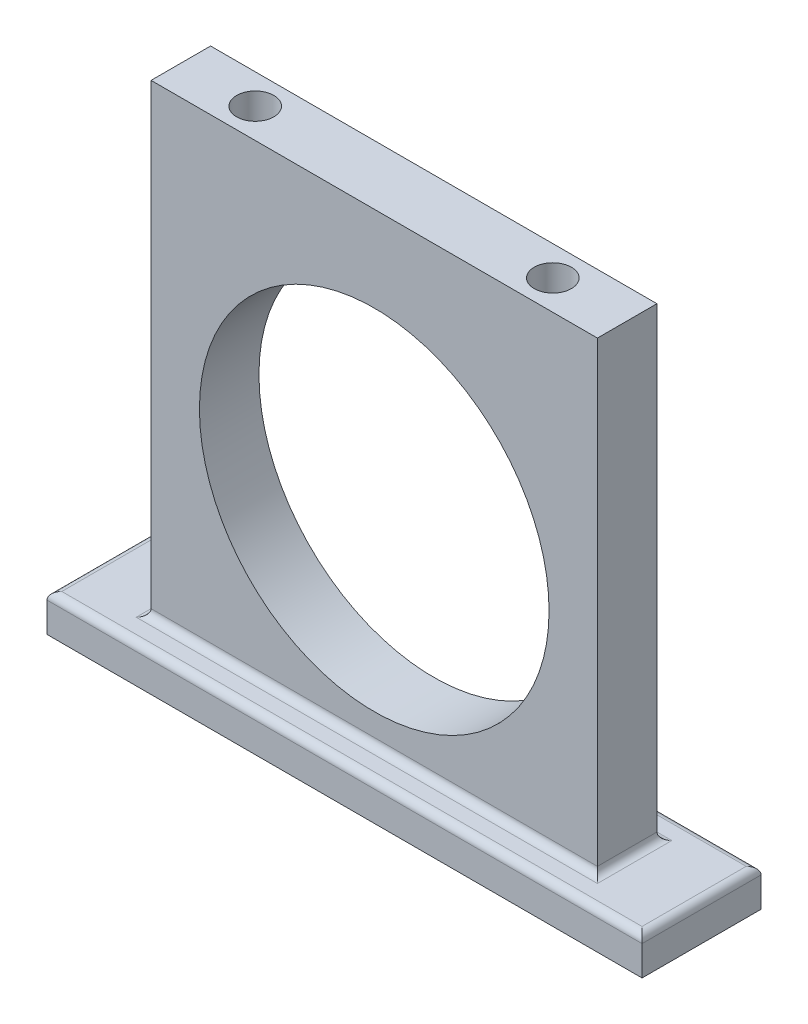
SolidWorks part; units mm, degrees
ref_plane "前视基准面" through (0, 0, 0) normal (0, 0, 1) x (1, 0, 0)
ref_plane "上视基准面" through (0, 0, 0) normal (0, 1, 0) x (1, 0, 0)
ref_plane "右视基准面" through (0, 0, 0) normal (1, 0, 0) x (0, 0, -1)
sketch "草图1" plane through (0, 0, 0) normal (0, 0, 1) x (1, 0, 0)
  line L0 (30, -32.5) -> (-30, -32.5)
  line L1 (-30, 0) -> (-30, -32.5)
  line L2 (-30, 0) -> (-30, 35)
  line L3 (-30, 35) -> (30, 35)
  line L4 (30, 35) -> (30, -32.5)
  line L5 (0, 35) -> (0, -47.189) construction
  circle A0 centre (0, 0) radius 23.5
  dimension "D1" = 32.5
  dimension "D3" = 60
  dimension "D2" = 35
extrude "凸台-拉伸1" add sketch "草图1" along normal blind 8
sketch "草图2" plane through (30, 0, 0) normal (1, 0, 0) x (0, 0, -1)
  line L0 (-4, -32.5) -> (-4, -46.3378) construction
  line L1 (-8, -32.5) -> (0, -32.5) construction
  line L3 (-12, -32.5) -> (4, -32.5)
  line L4 (-12, -32.5) -> (-12, -27.5)
  line L5 (-12, -27.5) -> (4, -27.5)
  line L6 (4, -32.5) -> (4, -27.5)
  point P8 (-4, -32.5)
extrude "凸台-拉伸2" add sketch "草图2" against normal blind 70
ref_plane "基准面4" through (0, 0, 0) normal (-1, 0, 0) x (0, 0, 1)
mirror "镜向1" about plane through (0, 0, 0) normal (-1, 0, 0) of "凸台-拉伸2"
fillet "圆角2" radius 1 8 edges at (0, -27.5, 12) (-40, -27.5, 4) (0, -27.5, -4) (40, -27.5, 4) (-30, -27.5, 4) (0, -27.5, 8) (30, -27.5, 4) (0, -27.5, 0)
sketch "草图3" plane through (0, 35, 0) normal (0, 1, 0) x (1, 0, 0)
  line L0 (-30, -4) -> (36.4193, -4) construction
  line L1 (-30, -8) -> (-30, 0) construction
  line L2 (-20, -22.8958) -> (-20, 13.0558)
  line L3 (0, -8) -> (0, 10.9623) construction
  line L4 (30, -8) -> (-30, -8) construction
  line L5 (20, -22.8958) -> (20, 13.0558)
  dimension "D1" = 20
ref_point "点1"
ref_point "点2"
hole_wizard "M6 螺纹孔1" positions "草图13" profile "草图14" tap size "M6" standard "GB"
sketch "草图13" plane through (0, 35, 0) normal (0, 1, 0) x (1, 0, 0)
  point P0 (-20, -4)
  point P3 (20, -4)
sketch "草图14" plane through (-20, 35, 4) normal (1, 0, 0) x (0, 0, 1)
  line L0 (0, 0) -> (0, 8.5022)
  line L1 (0, 8.5022) -> (2.5, 7)
  line L2 (2.5, 7) -> (2.5, 0)
  line L5 (2.5, 0) -> (0, 0)
  line L10 (0, 8.5022) -> (-2.5, 7) construction
  line L11 (0, -6.35) -> (0, 107.95) construction
  dimension "螺纹孔钻头直径" = 5
  dimension "螺纹孔钻头深度" = 7
  dimension "导头角度" = 118
cosmetic thread "孔螺蚊线1" parameters "D1"=3, "D2"=6
cosmetic thread "孔螺蚊线2" parameters "D1"=3, "D2"=6
